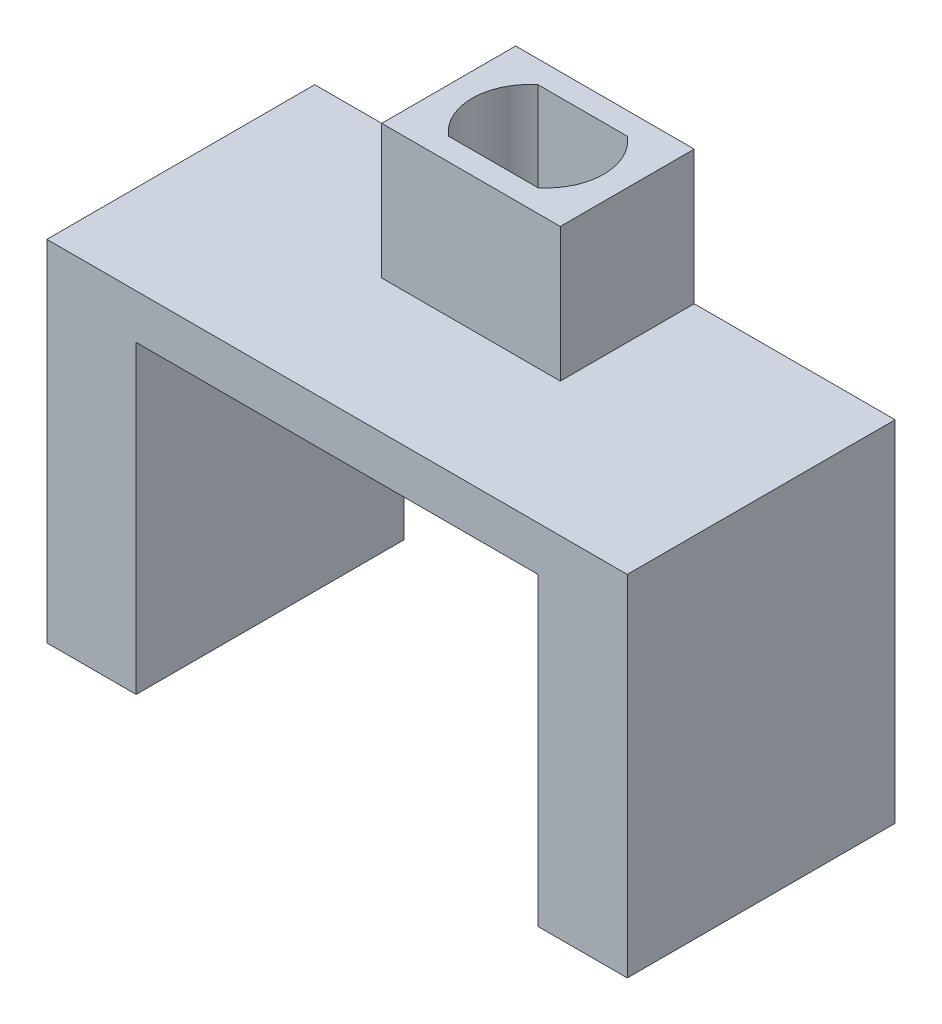
SolidWorks part; units mm, degrees
ref_plane "Front Plane" through (0, 0, 0) normal (0, 0, 1) x (1, 0, 0)
ref_plane "Top Plane" through (0, 0, 0) normal (0, 1, 0) x (1, 0, 0)
ref_plane "Right Plane" through (0, 0, 0) normal (1, 0, 0) x (0, 0, -1)
sketch "Sketch1" plane through (0, 0, 0) normal (0, 1, 0) x (1, 0, 0)
  line L1 (-32.5, -15) -> (32.5, -15)
  line L2 (-32.5, -15) -> (-32.5, 15)
  line L3 (-32.5, 15) -> (32.5, 15)
  line L4 (32.5, -15) -> (32.5, 15)
  line L5 (-32.5, -15) -> (32.5, 15) construction
  line L6 (-32.5, 15) -> (32.5, -15) construction
  point P0 (0, 0)
  dimension "D1" = 30
  dimension "D2" = 65
extrude "Boss-Extrude1" add sketch "Sketch1" along normal blind 5
sketch "Sketch2" plane through (0, 5, 0) normal (0, 1, 0) x (1, 0, 0)
  line L0 (32.5, 15) -> (-32.5, 15) construction
  line L5 (-10, 15) -> (10, 15)
  line L6 (-10, 15) -> (-10, 0)
  line L7 (-10, 0) -> (10, 0)
  line L8 (10, 15) -> (10, 0)
  line L9 (-10, 15) -> (10, 0) construction
  line L10 (-10, 0) -> (10, 15) construction
  point P0 (0, 7.5)
  point P5 (0, 0)
  point P6 (0, 0)
  point P9 (0, 15)
  dimension "D1" = 15
  dimension "D2" = 20
extrude "Boss-Extrude2" add sketch "Sketch2" along normal blind 15
sketch "Sketch3" plane through (0, 20, 0) normal (0, 1, 0) x (1, 0, 0)
  line L0 (-10, 15) -> (-10, 0) construction
  line L1 (-5, 2.5) -> (5, 2.5)
  line L3 (-5, 12.5) -> (5, 12.5)
  line L5 (-5, 2.5) -> (5, 12.5) construction
  line L6 (-5, 12.5) -> (5, 2.5) construction
  line L7 (10, 15) -> (-10, 15) construction
  arc A1 (-5, 12.5) -> (-5, 2.5) centre (-0.9262, 7.5) ccw
  arc A3 (5, 2.5) -> (5, 12.5) centre (0.9262, 7.5) ccw
  point P0 (0, 7.5)
  point P5 (0, 0)
  point P6 (0, 0)
  point P8 (0, 0)
  point P10 (0, 0)
  point P11 (0, 0)
  point P14 (-10, 7.5)
  point P15 (0, 0)
  point P18 (0, 15)
  dimension "D3" = 1.8525
  dimension "D1" = 10
  dimension "D2" = 10
extrude "Cut-Extrude1" cut sketch "Sketch3" against normal up to surface (15 mm away) up to face at (0, 5, -3.75)
sketch "Sketch4" plane through (0, 5, 0) normal (0, 1, 0) x (1, 0, 0)
  line L0 (-10, 15) -> (-10, 0) construction
  line L1 (-10, 0) -> (10, 0) construction
  circle A1 centre (0, 7.5) radius 1.8526
  point P3 (0, 0)
  point P4 (0, 0)
  point P7 (-10, 7.5)
  point P8 (0, 0)
  point P11 (0, 0)
extrude "Cut-Extrude2" cut sketch "Sketch4" against normal through all
sketch "Sketch5" plane through (0, 0, 0) normal (0, -1, 0) x (1, 0, 0)
  line L0 (-32.5, 15) -> (32.5, 15) construction
  line L1 (32.5, -15) -> (22.5, -15)
  line L2 (32.5, -15) -> (32.5, 15)
  line L3 (32.5, 15) -> (22.5, 15)
  line L4 (22.5, -15) -> (22.5, 15)
  line L6 (-32.5, -15) -> (-22.5, -15)
  line L7 (-32.5, -15) -> (-32.5, 15)
  line L8 (-32.5, 15) -> (-22.5, 15)
  line L9 (-22.5, -15) -> (-22.5, 15)
  dimension "D1" = 10
extrude "Boss-Extrude3" add sketch "Sketch5" along normal up to surface (34.1462 mm away)
